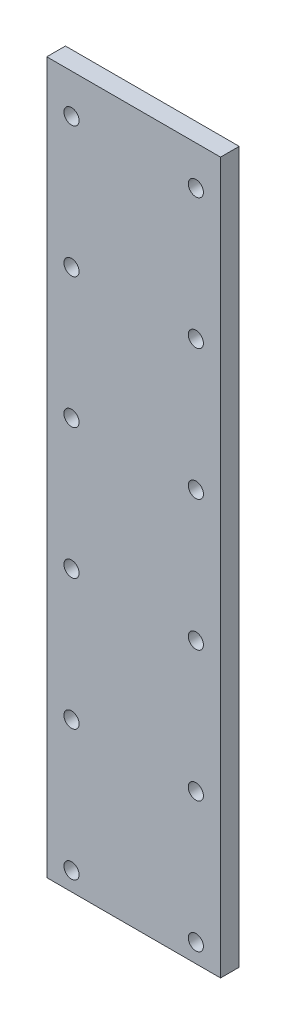
SolidWorks part; units mm, degrees
ref_plane "Front Plane" through (0, 0, 0) normal (0, 0, 1) x (1, 0, 0)
ref_plane "Top Plane" through (0, 0, 0) normal (0, 1, 0) x (1, 0, 0)
ref_plane "Right Plane" through (0, 0, 0) normal (1, 0, 0) x (0, 0, -1)
sketch "Sketch1" plane through (0, 0, 0) normal (0, 0, 1) x (1, 0, 0)
  line L1 (-13.97, -57.15) -> (13.97, -57.15)
  line L2 (-13.97, -57.15) -> (-13.97, 57.15)
  line L3 (-13.97, 57.15) -> (13.97, 57.15)
  line L4 (13.97, -57.15) -> (13.97, 57.15)
  line L5 (-13.97, -57.15) -> (13.97, 57.15) construction
  line L6 (-13.97, 57.15) -> (13.97, -57.15) construction
  point P0 (0, 0)
  dimension "D1" = 27.94
  dimension "D2" = 114.3
extrude "Boss-Extrude1" add sketch "Sketch1" along normal blind 3
sketch "Sketch2" plane through (0, 0, 3) normal (0, 0, 1) x (1, 0, 0)
  line L0 (-9.9949, -54.15) -> (0, -54.15) construction
  line L3 (0, -54.15) -> (9.9949, -54.15) construction
  line L4 (0, -57.15) -> (0, 0) construction
  line L5 (-13.97, -57.15) -> (13.97, -57.15) construction
  circle A0 centre (-9.9949, -54.15) radius 1.2192
  circle A1 centre (9.9949, -54.15) radius 1.2192
  point P12 (0, -54.15)
  dimension "D2" = 3
  dimension "D3" = 2.4384
  dimension "D4" = 2.4384
  dimension "D1" = 19.9898
extrude "Cut-Extrude1" cut sketch "Sketch2" against normal through all
pattern_linear "LPattern1" count 6 spacing 21 along (0, 1, 0) of "Cut-Extrude1"
